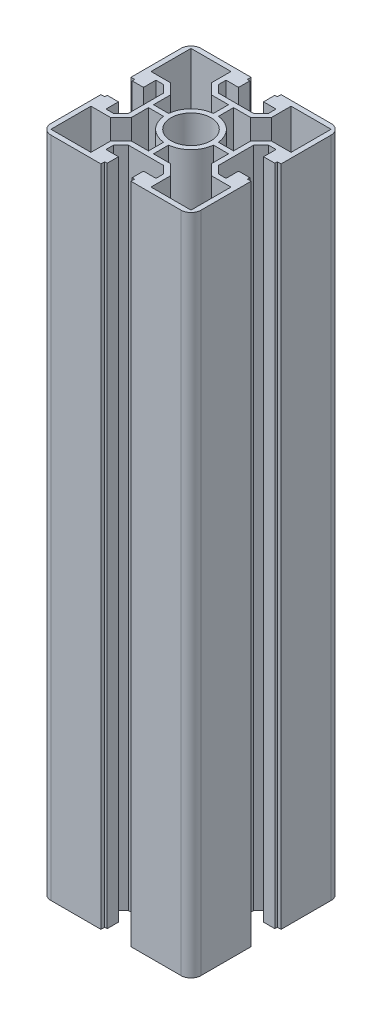
SolidWorks part; units mm, degrees
ref_plane "前视基准面" through (0, 0, 0) normal (0, 0, 1) x (1, 0, 0)
ref_plane "上视基准面" through (0, 0, 0) normal (0, 1, 0) x (1, 0, 0)
ref_plane "右视基准面" through (0, 0, 0) normal (1, 0, 0) x (0, 0, -1)
sketch "草图1" plane through (0, 0, 0) normal (0, 1, 0) x (1, 0, 0)
  line L0 (0, 32.6515) -> (0, -47.5) construction
  line L2 (-54.5455, 0) -> (57.7273, 0) construction
  line L82 (-16, 1) -> (-9.9499, 1)
  line L83 (-30, 6) -> (-28.5, 6)
  line L88 (-16, 1) -> (-16, 7.8284)
  line L89 (-16, 7.8284) -> (-20.1716, 12)
  line L90 (-20.1716, 12) -> (-28, 12)
  line L91 (-28, 12) -> (-28, 28)
  line L92 (-28, 28) -> (-12, 28)
  line L93 (-12, 28) -> (-12, 20.1716)
  line L94 (-12, 20.1716) -> (-7.8284, 16)
  line L95 (-7.8284, 16) -> (-1, 16)
  line L96 (-1, 16) -> (-1, 9.9499)
  line L97 (1, 9.9499) -> (1, 16)
  line L98 (1, 16) -> (7.8284, 16)
  line L99 (7.8284, 16) -> (12, 20.1716)
  line L100 (12, 20.1716) -> (12, 28)
  line L101 (12, 28) -> (28, 28)
  line L102 (28, 28) -> (28, 12)
  line L103 (28, 12) -> (20.1716, 12)
  line L104 (20.1716, 12) -> (16, 7.8284)
  line L105 (16, 7.8284) -> (16, 1)
  line L106 (16, 1) -> (9.9499, 1)
  line L107 (9.9499, -1) -> (16, -1)
  line L108 (16, -1) -> (16, -7.8284)
  line L109 (16, -7.8284) -> (20.1716, -12)
  line L110 (20.1716, -12) -> (28, -12)
  line L111 (28, -12) -> (28, -28)
  line L112 (28, -28) -> (12, -28)
  line L113 (12, -28) -> (12, -20.1716)
  line L114 (12, -20.1716) -> (7.8284, -16)
  line L115 (7.8284, -16) -> (1, -16)
  line L116 (1, -16) -> (1, -9.9499)
  line L117 (-1, -9.9499) -> (-1, -16)
  line L118 (-1, -16) -> (-7.8284, -16)
  line L119 (-7.8284, -16) -> (-12, -20.1716)
  line L120 (-12, -20.1716) -> (-12, -28)
  line L121 (-12, -28) -> (-28, -28)
  line L122 (-28, -28) -> (-28, -12)
  line L123 (-28, -12) -> (-20.1716, -12)
  line L124 (-20.1716, -12) -> (-16, -7.8284)
  line L125 (-16, -7.8284) -> (-16, -1)
  line L126 (-28.5, 6) -> (-28.5, 5)
  line L127 (-28.5, 5) -> (-24, 5)
  line L128 (-24, 5) -> (-24, 10)
  line L129 (-24, 10) -> (-21, 10)
  line L130 (-21, 10) -> (-18, 7)
  line L131 (-18, 7) -> (-18, -7)
  line L132 (-18, -7) -> (-21, -10)
  line L133 (-21, -10) -> (-24, -10)
  line L134 (-24, -10) -> (-24, -5)
  line L135 (-24, -5) -> (-28.5, -5)
  line L136 (-28.5, -5) -> (-28.5, -6)
  line L137 (-28.5, -6) -> (-30, -6)
  line L138 (-30, -6) -> (-30, -26)
  line L139 (-26, -30) -> (-6, -30)
  line L140 (-6, -30) -> (-6, -28.5)
  line L141 (-6, -28.5) -> (-5, -28.5)
  line L142 (-5, -28.5) -> (-5, -24)
  line L143 (-5, -24) -> (-10, -24)
  line L144 (-10, -24) -> (-10, -21)
  line L145 (-10, -21) -> (-7, -18)
  line L146 (-7, -18) -> (7, -18)
  line L147 (7, -18) -> (10, -21)
  line L148 (10, -21) -> (10, -24)
  line L149 (10, -24) -> (5, -24)
  line L150 (5, -24) -> (5, -28.5)
  line L151 (5, -28.5) -> (6, -28.5)
  line L152 (6, -28.5) -> (6, -30)
  line L153 (6, -30) -> (26, -30)
  line L154 (30, -26) -> (30, -6)
  line L155 (30, -6) -> (28.5, -6)
  line L156 (28.5, -6) -> (28.5, -5)
  line L157 (28.5, -5) -> (24, -5)
  line L158 (24, -5) -> (24, -10)
  line L159 (24, -10) -> (21, -10)
  line L160 (21, -10) -> (18, -7)
  line L161 (18, -7) -> (18, 7)
  line L162 (18, 7) -> (21, 10)
  line L163 (21, 10) -> (24, 10)
  line L164 (24, 10) -> (24, 5)
  line L165 (24, 5) -> (28.5, 5)
  line L166 (28.5, 5) -> (28.5, 6)
  line L167 (28.5, 6) -> (30, 6)
  line L168 (30, 6) -> (30, 26)
  line L169 (26, 30) -> (6, 30)
  line L170 (6, 30) -> (6, 28.5)
  line L171 (6, 28.5) -> (5, 28.5)
  line L172 (5, 28.5) -> (5, 24)
  line L173 (5, 24) -> (10, 24)
  line L174 (10, 24) -> (10, 21)
  line L175 (10, 21) -> (7, 18)
  line L176 (7, 18) -> (-7, 18)
  line L177 (-7, 18) -> (-10, 21)
  line L178 (-10, 21) -> (-10, 24)
  line L179 (-10, 24) -> (-5, 24)
  line L180 (-5, 24) -> (-5, 28.5)
  line L181 (-5, 28.5) -> (-6, 28.5)
  line L182 (-6, 28.5) -> (-6, 30)
  line L183 (-6, 30) -> (-26, 30)
  line L184 (-30, 26) -> (-30, 6)
  line L185 (-16, -1) -> (-9.9499, -1)
  arc A41 (-9.9499, -1) -> (-1, -9.9499) centre (0, 0) ccw
  circle A42 centre (0, 0) radius 8
  arc A43 (-26, -30) -> (-30, -26) centre (-26, -26) cw
  arc A44 (26, 30) -> (30, 26) centre (26, 26) cw
  arc A45 (-26, 30) -> (-30, 26) centre (-26, 26) ccw
  arc A46 (26, -30) -> (30, -26) centre (26, -26) ccw
  arc A47 (9.9499, 1) -> (1, 9.9499) centre (0, 0) ccw
  arc A48 (-1, 9.9499) -> (-9.9499, 1) centre (0, 0) ccw
  arc A49 (1, -9.9499) -> (9.9499, -1) centre (0, 0) ccw
extrude "凸台-拉伸1" add sketch "草图1" along normal blind 265
ref_plane "基准面1" through (0, 15, 0) normal (0, 1, 0) x (1, 0, 0)
